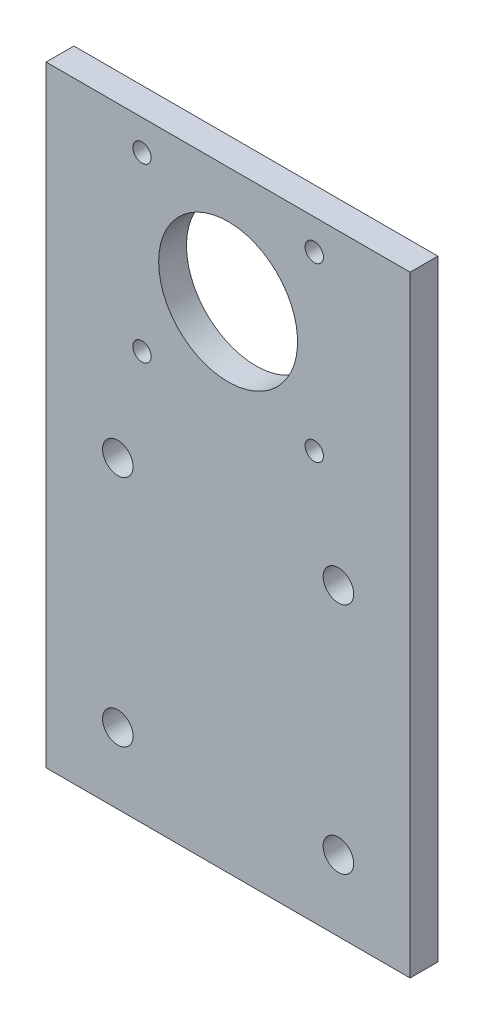
SolidWorks part; units mm, degrees
ref_plane "Plan de face" through (0, 0, 0) normal (0, 0, 1) x (1, 0, 0)
ref_plane "Plan de dessus" through (0, 0, 0) normal (0, 1, 0) x (1, 0, 0)
ref_plane "Plan de droite" through (0, 0, 0) normal (1, 0, 0) x (0, 0, -1)
sketch "Sketch1" plane through (0, 0, 0) normal (0, 0, 1) x (1, 0, 0)
  line L1 (32.75, -55) -> (-32.75, -55)
  line L2 (32.75, -55) -> (32.75, 55)
  line L3 (32.75, 55) -> (-32.75, 55)
  line L4 (-32.75, -55) -> (-32.75, 55)
  line L5 (32.75, -55) -> (-32.75, 55) construction
  line L6 (32.75, 55) -> (-32.75, -55) construction
  point P0 (0, 0)
  dimension "D1" = 65.5
  dimension "D2" = 110
extrude "Boss-Extrude1" add sketch "Sketch1" along normal blind 5
sketch "Sketch2" plane through (0, 0, 0) normal (0, 0, -1) x (-1, 0, 0)
  circle A0 centre (0, 34.025) radius 12.5
  dimension "D1" = 25
extrude "Cut-Extrude1" cut sketch "Sketch2" against normal through all
sketch "Sketch3" plane through (0, 0, 0) normal (0, 0, -1) x (-1, 0, 0)
  circle A0 centre (-15.5, 49.525) radius 1.65
  circle A1 centre (-15.5, 18.525) radius 1.65
  circle A2 centre (15.5, 18.525) radius 1.65
  circle A3 centre (15.5, 49.525) radius 1.65
  dimension "D1" = 3.3
  dimension "D2" = 3.3
  dimension "D3" = 3.3
  dimension "D4" = 3.3
extrude "Cut-Extrude2" cut sketch "Sketch3" against normal through all
sketch "Sketch4" plane through (0, 0, 0) normal (0, 0, -1) x (-1, 0, 0)
  line L0 (32.75, -55) -> (-32.75, -55) construction
  circle A0 centre (-19.85, -0.25) radius 2.75
  circle A1 centre (19.85, -0.25) radius 2.75
  circle A2 centre (19.85, -42.25) radius 2.75
  circle A3 centre (-19.85, -42.25) radius 2.75
  dimension "D1" = 5.5
  dimension "D2" = 5.5
  dimension "D3" = 5.5
  dimension "D4" = 5.5
  dimension "D6" = 42
  dimension "D5" = 12.75
  dimension "D7" = 42
extrude "Cut-Extrude3" cut sketch "Sketch4" against normal through all
